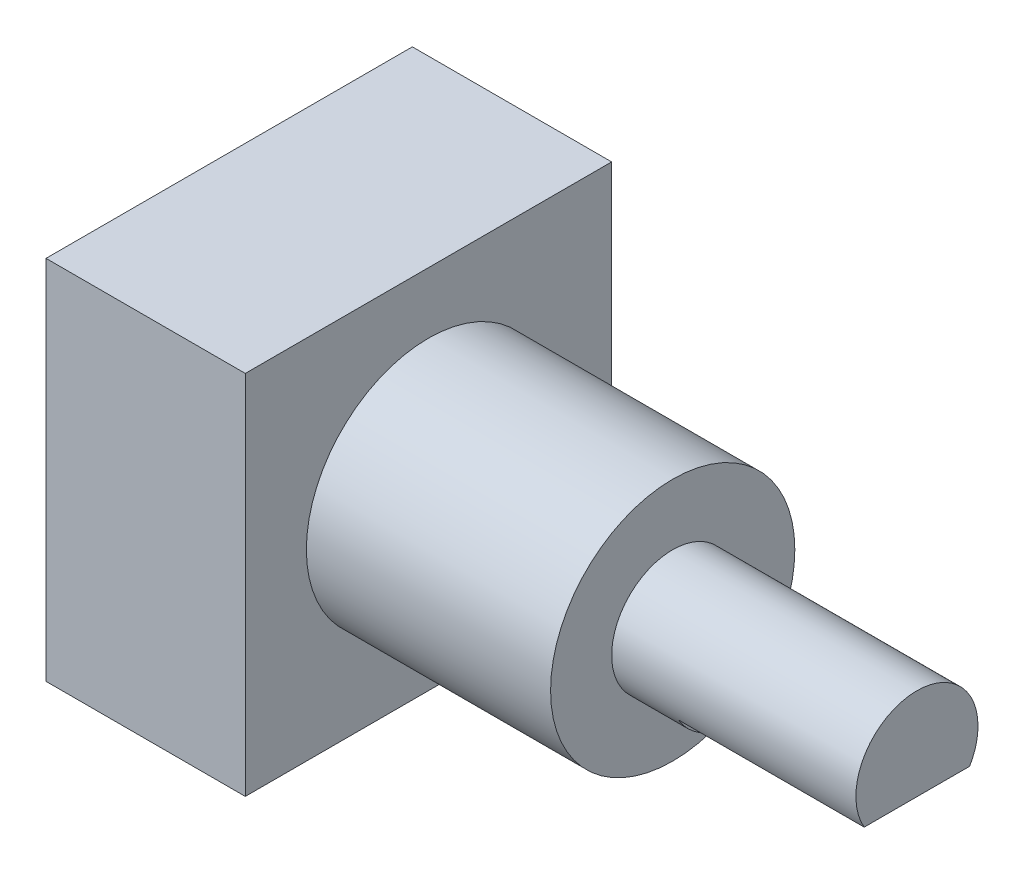
SolidWorks part; units mm, degrees
ref_plane "Front" through (0, 0, 0) normal (0, 0, 1) x (1, 0, 0)
ref_plane "Top" through (0, 0, 0) normal (0, 1, 0) x (1, 0, 0)
ref_plane "Right" through (0, 0, 0) normal (1, 0, 0) x (0, 0, -1)
sketch "Sketch1" plane through (0, 0, 0) normal (0, 0, 1) x (1, 0, 0)
  line L0 (0, 3.175) -> (6.35, 3.175)
  line L1 (6.35, 3.175) -> (6.35, 1.5875)
  line L2 (6.35, 1.5875) -> (12.7, 1.5875)
  line L3 (12.7, 1.5875) -> (12.7, 0)
  line L4 (12.7, 0) -> (0, 0)
  line L5 (0, 0) -> (0, 3.175)
  line L6 (0, 0) -> (-11.3591, 0) construction
  dimension "D1" = 6.35
  dimension "D2" = 3.175
  dimension "D3" = 12.7
  dimension "D4" = 6.35
revolve "Revolve1" add sketch "Sketch1" angle 360 about L6
sketch "Sketch2" plane through (0, 0, 0) normal (1, 0, 0) x (0, 0, -1)
  line L1 (-4.7625, -4.7625) -> (4.7625, -4.7625)
  line L2 (-4.7625, -4.7625) -> (-4.7625, 4.7625)
  line L3 (-4.7625, 4.7625) -> (4.7625, 4.7625)
  line L4 (4.7625, -4.7625) -> (4.7625, 4.7625)
  line L5 (-4.7625, -4.7625) -> (4.7625, 4.7625) construction
  line L6 (-4.7625, 4.7625) -> (4.7625, -4.7625) construction
  point P0 (0, 0)
  dimension "D1" = 9.525
extrude "Boss-Extrude1" add sketch "Sketch2" against normal blind 5.1816
sketch "Sketch4" plane through (12.7, 0, 0) normal (1, 0, 0) x (0, 0, -1)
  line L0 (-1.3711, -0.8001) -> (1.3711, -0.8001)
  line L1 (0, -0.8001) -> (0, 1.5875) construction
  circle A0 centre (0, 0) radius 1.5875 construction
  arc A1 (-1.3711, -0.8001) -> (1.3711, -0.8001) centre (0, 0) ccw
  dimension "D1" = 2.3876
extrude "Cut-Extrude1" cut sketch "Sketch4" against normal blind 4.826
